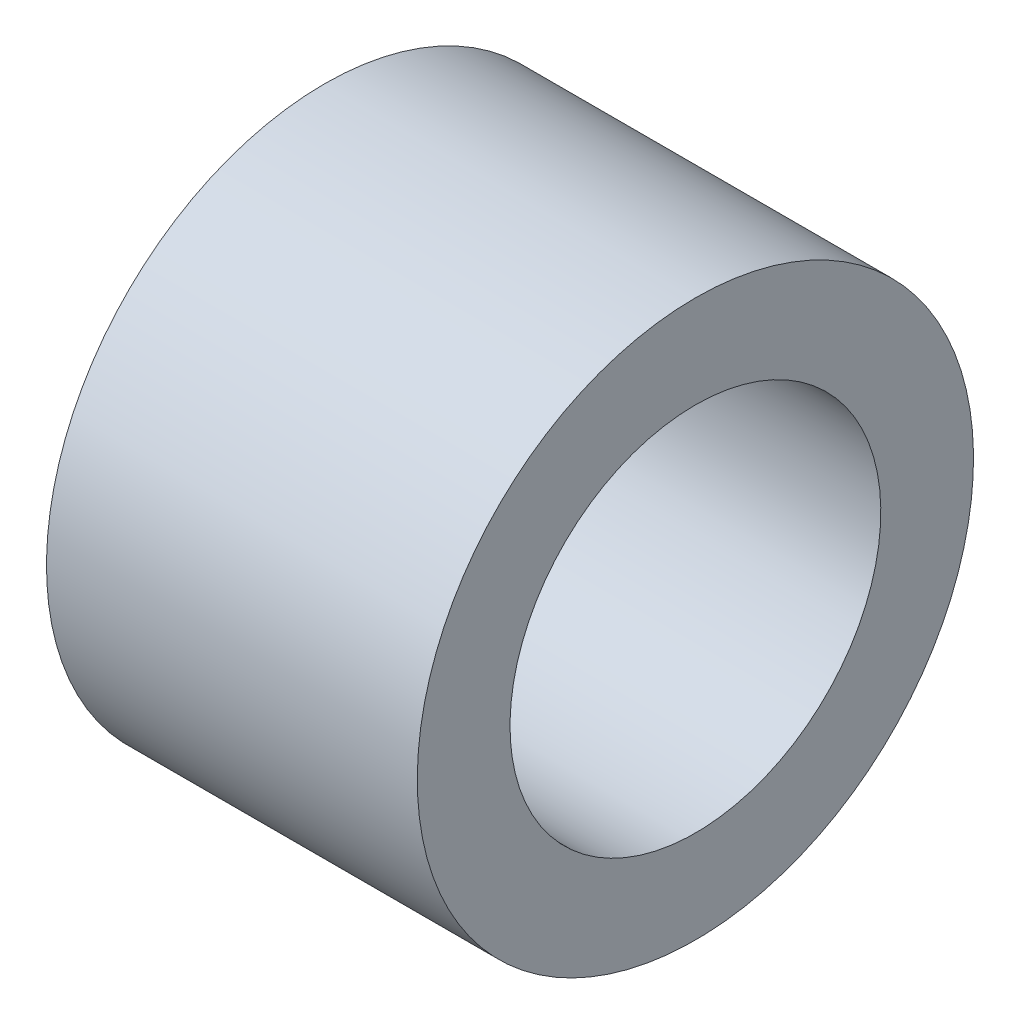
SolidWorks part; units mm, degrees
ref_plane "Front Plane" through (0, 0, 0) normal (0, 0, 1) x (1, 0, 0)
ref_plane "Top Plane" through (0, 0, 0) normal (0, 1, 0) x (1, 0, 0)
ref_plane "Right Plane" through (0, 0, 0) normal (1, 0, 0) x (0, 0, -1)
sketch "Sketch1" plane through (0, 0, 0) normal (0, 0, 1) x (1, 0, 0)
  line L0 (0, 0) -> (0, 6)
  line L1 (0, 6) -> (8, 6)
  line L2 (8, 6) -> (8, 4)
  line L3 (8, 4) -> (1, 4)
  line L4 (1, 4) -> (1, 0)
  line L5 (1, 0) -> (0, 0)
  dimension "D1" = 6
  dimension "D2" = 4
  dimension "D3" = 8
  dimension "D4" = 1
revolve "Revolve1" add sketch "Sketch1" angle 360 about L5
